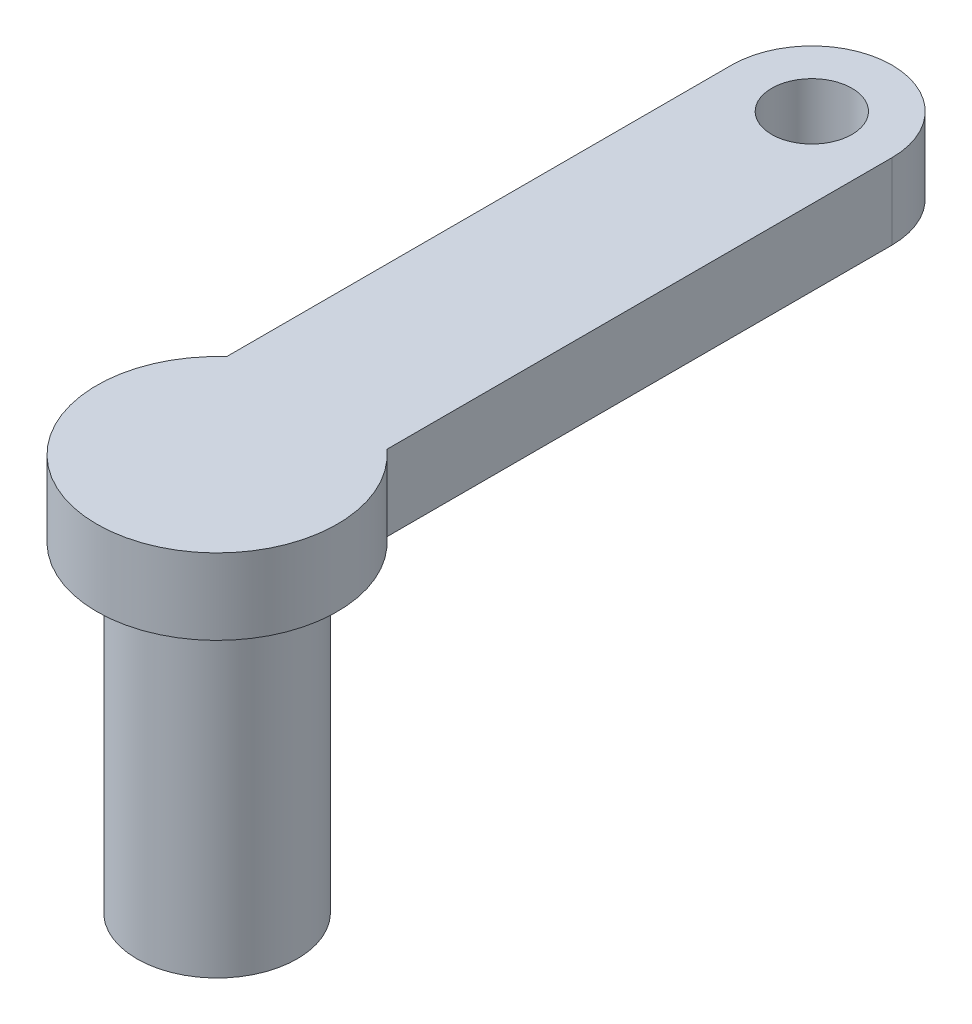
SolidWorks part; units mm, degrees
ref_plane "Front Plane" through (0, 0, 0) normal (0, 0, 1) x (1, 0, 0)
ref_plane "Top Plane" through (0, 0, 0) normal (0, 1, 0) x (1, 0, 0)
ref_plane "Right Plane" through (0, 0, 0) normal (1, 0, 0) x (0, 0, -1)
sketch "Sketch1" plane through (0, 0, 0) normal (0, 1, 0) x (1, 0, 0)
  line L0 (0, -8.635) -> (0, 8.635) construction
  line L2 (-39.6875, 44.372) -> (-39.6875, 294.372)
  line L4 (39.6875, 44.372) -> (39.6875, 294.372)
  arc A0 (-39.6875, 44.372) -> (39.6875, 44.372) centre (0, 0) ccw
  arc A2 (39.6875, 294.372) -> (-39.6875, 294.372) centre (0, 294.372) ccw
  circle A3 centre (0, 294.372) radius 19.8438
  dimension "Grasper Spacing" = 59.5312
  dimension "Knuckle Hole Diameter" = 39.6875
  dimension "Grasper Link1 Width" = 79.375
  dimension "Grasper Link1 Width Div2" = 39.6875
  dimension "Grasper Link Length" = 250
extrude "Boss-Extrude1" add sketch "Sketch1" along normal blind 37.5 contours A3 | L4 A2 L2 A0
sketch "Sketch2" plane through (0, 0, 0) normal (0, -1, 0) x (1, 0, 0)
  circle A0 centre (0, 0) radius 39.6875
  dimension "Grasper Diameter" = 79.375
extrude "Boss-Extrude2" add sketch "Sketch2" along normal blind 158.75
